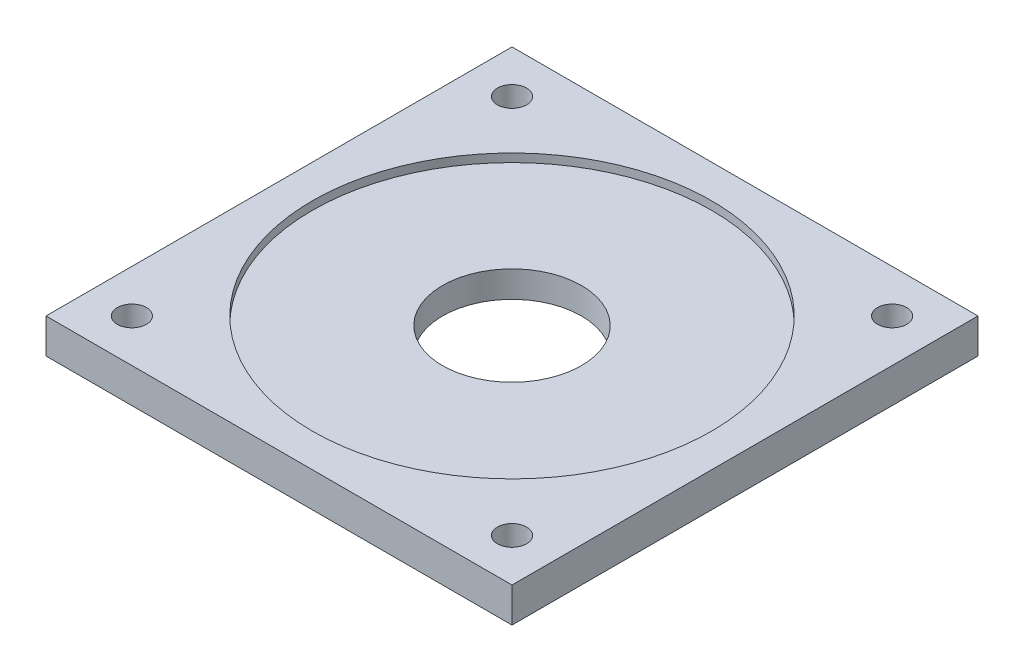
SolidWorks part; units mm, degrees
ref_plane "Front" through (0, 0, 0) normal (0, 0, 1) x (1, 0, 0)
ref_plane "Top" through (0, 0, 0) normal (0, 1, 0) x (1, 0, 0)
ref_plane "Right" through (0, 0, 0) normal (1, 0, 0) x (0, 0, -1)
sketch "Sketch1" plane through (0, 0, 0) normal (0, 1, 0) x (1, 0, 0)
  line L1 (-42.6, -42.6) -> (42.6, -42.6)
  line L2 (-42.6, -42.6) -> (-42.6, 42.6)
  line L3 (-42.6, 42.6) -> (42.6, 42.6)
  line L4 (42.6, -42.6) -> (42.6, 42.6)
  line L5 (-42.6, -42.6) -> (42.6, 42.6) construction
  line L6 (-42.6, 42.6) -> (42.6, -42.6) construction
  point P0 (0, 0)
  dimension "D1" = 85.2
  dimension "D2" = 85.2
extrude "Boss-Extrude1" add sketch "Sketch1" along normal blind 6.35
sketch "Sketch2" plane through (0, 6.35, 0) normal (0, 1, 0) x (1, 0, 0)
  circle A0 centre (0, 0) radius 36.49
  dimension "D1" = 72.98
extrude "Cut-Extrude1" cut sketch "Sketch2" against normal up to next
sketch "Sketch4" plane through (-42.6, 0, 0) normal (-1, 0, 0) x (0, 0, 1)
  line L4 (-42.6, 0) -> (42.6, 0)
  line L5 (42.6, 0) -> (42.6, 6.35)
  line L6 (42.6, 6.35) -> (-42.6, 6.35)
  line L7 (-42.6, 6.35) -> (-42.6, 0)
  line L8 (-42.6, 0) -> (42.6, 0)
  line L9 (42.6, 0) -> (42.6, 6.35)
  line L10 (42.6, 6.35) -> (-42.6, 6.35)
  line L11 (-42.6, 6.35) -> (-42.6, 0)
  dimension "D1" = 0
sketch "Sketch5" plane through (0, 0, 0) normal (0, -1, 0) x (1, 0, 0)
  circle A0 centre (0, 0) radius 12.7
  circle A1 centre (0, 0) radius 36.49 construction
  circle A2 centre (0, 0) radius 36.49
  dimension "D1" = 25.4
extrude "Boss-Extrude2" add sketch "Sketch5" against normal blind 4.83
sketch "Sketch6" plane through (0, 0, 0) normal (0, -1, 0) x (1, 0, 0)
  line L0 (42.6, -42.6) -> (-42.6, -42.6) construction
  line L1 (-42.6, -42.6) -> (-42.6, 42.6) construction
  circle A0 centre (-34.75, -34.75) radius 2.665
  circle A1 centre (-34.75, 34.75) radius 2.665
  circle A2 centre (34.75, 34.75) radius 2.665
  circle A3 centre (34.75, -34.75) radius 2.665
  point P15 (0, 0)
  dimension "D1" = 7.85
  dimension "D2" = 7.85
  dimension "D3" = 5.33
  dimension "D4" = 4
extrude "Cut-Extrude2" cut sketch "Sketch6" against normal up to next
